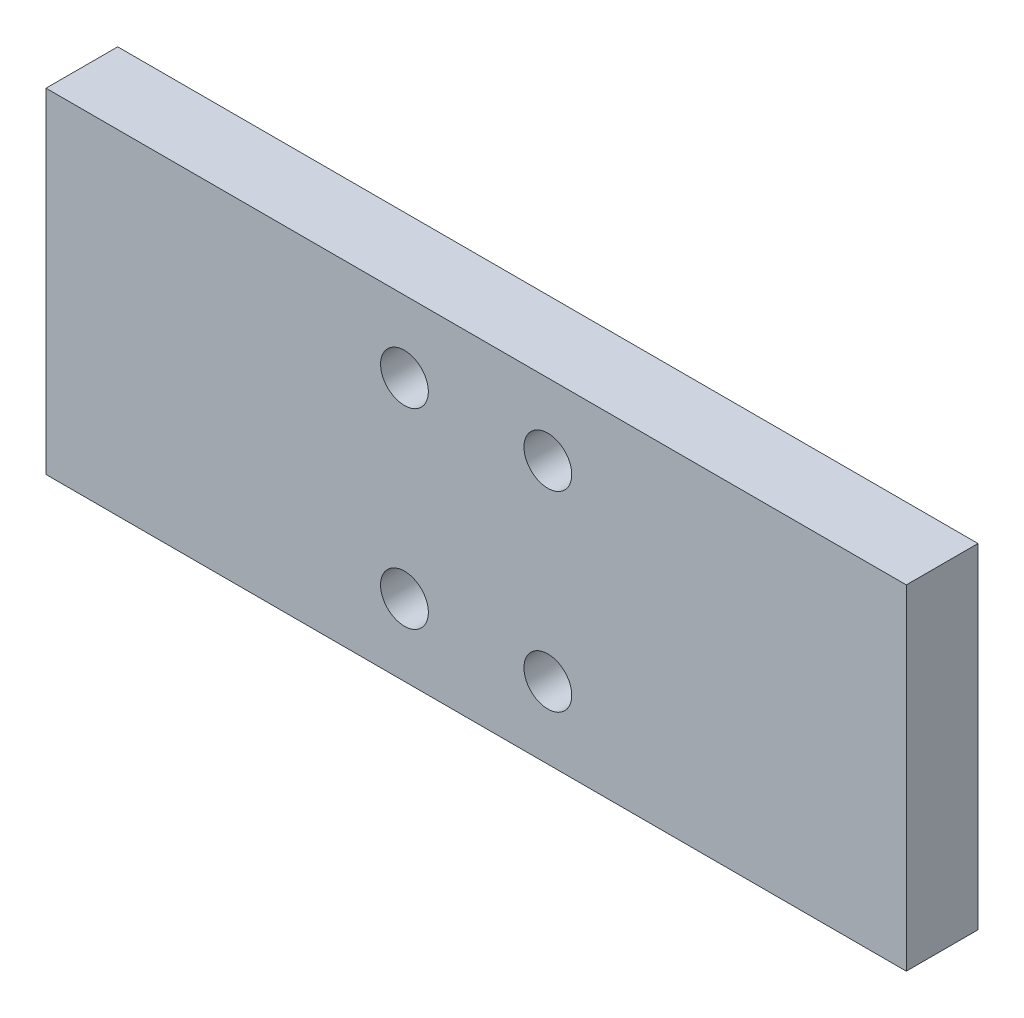
SolidWorks part; units mm, degrees
ref_plane "前视基准面" through (0, 0, 0) normal (0, 0, 1) x (1, 0, 0)
ref_plane "上视基准面" through (0, 0, 0) normal (0, 1, 0) x (1, 0, 0)
ref_plane "右视基准面" through (0, 0, 0) normal (1, 0, 0) x (0, 0, -1)
other "Configuration Table"
sketch "草图1" plane through (0, 0, 0) normal (0, 0, 1) x (1, 0, 0)
  line L0 (-91.3811, 0) -> (0, 0) construction
  line L1 (-90, 35) -> (90, 35)
  line L2 (-90, 35) -> (-90, -35)
  line L3 (-90, -35) -> (90, -35)
  line L4 (90, 35) -> (90, -35)
  line L5 (-90, 35) -> (90, -35) construction
  line L6 (-90, -35) -> (90, 35) construction
  line L7 (0, 0) -> (0, 35) construction
  circle A0 centre (-15, 20) radius 5
  circle A1 centre (15, 20) radius 5
  circle A2 centre (15, -20) radius 5
  circle A3 centre (-15, -20) radius 5
  point P0 (0, 0)
  dimension "D3" = 10
  dimension "D1" = 180
  dimension "D2" = 70
  dimension "D4" = 40
  dimension "D5" = 30
extrude "凸台-拉伸1" add sketch "草图1" along normal mid plane 15
